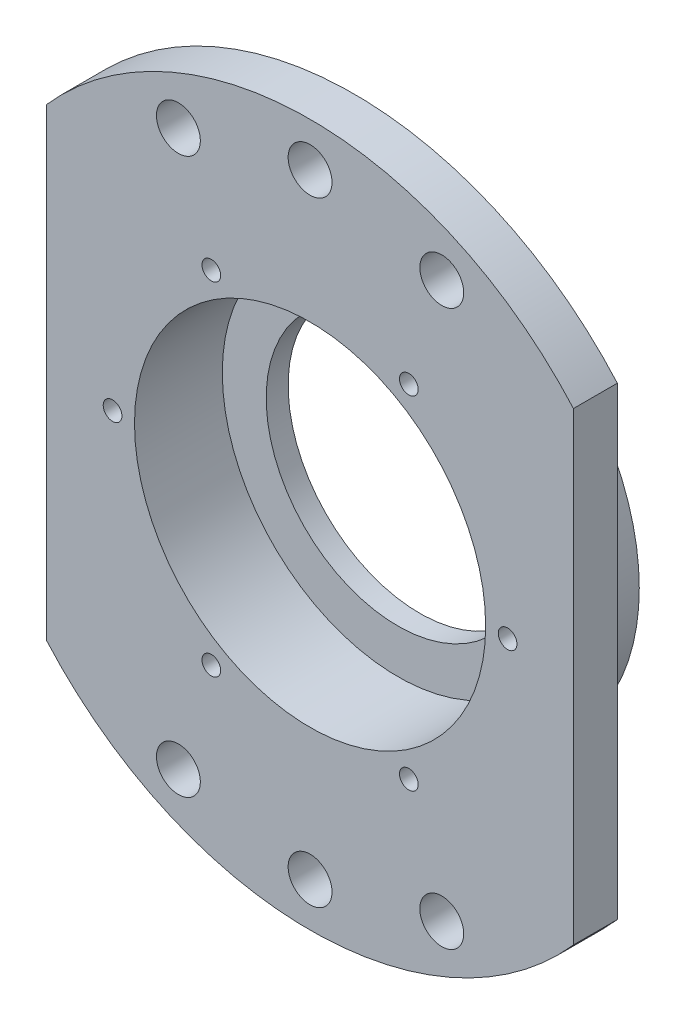
SolidWorks part; units mm, degrees
material "6061-T6 (SS)"
ref_plane "Front Plane" through (0, 0, 0) normal (0, 0, 1) x (1, 0, 0)
ref_plane "Top Plane" through (0, 0, 0) normal (0, 1, 0) x (1, 0, 0)
ref_plane "Right Plane" through (0, 0, 0) normal (1, 0, 0) x (0, 0, -1)
ref_plane "Plane1" through (0, 0, 1.5875) normal (0, 0, -1) x (-1, 0, 0)
sketch "Sketch1" plane through (0, 0, 1.5875) normal (0, 0, -1) x (-1, 0, 0)
  line L0 (38.1, -33.601) -> (38.1, 33.601)
  line L1 (-38.1, 33.601) -> (-38.1, -33.601)
  arc A0 (-38.1, -33.601) -> (38.1, -33.601) centre (0, 0) ccw
  arc A1 (38.1, 33.601) -> (-38.1, 33.601) centre (0, 0) ccw
extrude "Boss-Extrude1" add sketch "Sketch1" against normal blind 6.35
sketch "Sketch2" plane through (0, 0, 0) normal (0, 1, 0) x (1, 0, 0)
  line L0 (31.75, 7.9375) -> (0, 7.9375)
  line L1 (0, 7.9375) -> (0, -1.5875)
  line L2 (0, -1.5875) -> (31.75, -1.5875)
  line L3 (31.75, -1.5875) -> (31.75, 7.9375)
  line L4 (0, 7.9375) -> (0, -1.5875) construction
revolve "Revolve1" add sketch "Sketch2" angle 360 about L4
hole_wizard "2-4.5 Tapped Hole1" positions "Sketch8" profile "Sketch7" tap size "2-4.5" standard "ANSI Inch"
sketch "Sketch8" plane through (0, 0, 7.9375) normal (0, 0, 1) x (1, 0, 0)
  point P0 (0, 0)
sketch "Sketch7" plane through (0, 0, 7.9375) normal (1, 0, 0) x (0, -1, 0)
  line L0 (0, 0) -> (0, 15.875)
  line L1 (0, 15.875) -> (19.05, 15.875)
  line L3 (19.05, 15.875) -> (19.05, 12.7)
  line L4 (19.05, 12.7) -> (25.4, 12.7)
  line L5 (25.4, 12.7) -> (25.4, 0)
  line L7 (25.4, 0) -> (0, 0)
  line L11 (0, -6.35) -> (0, 107.95) construction
  dimension "Thru Tap Drill Dia." = 38.1
  dimension "Thru Tap Drill Depth" = 15.875
  dimension "Thread Major Dia." = 50.8
  dimension "Thread Depth" = 12.7
ref_plane "Plane2" through (0, 0, 7.9375) normal (0, 0, 1) x (1, 0, 0)
sketch "Sketch13" plane through (0, 0, 7.9375) normal (0, 0, 1) x (1, 0, 0)
  circle A0 centre (0, 44.45) radius 3.175
  circle A1 centre (0, 0) radius 25.4 construction
  dimension "D1" = 6.35
  dimension "D2" = 44.45
extrude "Cut-Extrude1" cut sketch "Sketch13" against normal through all
pattern_circular "CirPattern1" count 2 over 360 about axis through (0, 0, 0) along (0, 0, 1) of "Cut-Extrude1"
hole_wizard "#6-32 Tapped Hole1" positions "Sketch14" profile "Sketch15" tap size "#6-32" standard "ANSI Inch" end condition through all
sketch "Sketch14" plane through (0, 0, 7.9375) normal (0, 0, 1) x (1, 0, 0)
  circle A0 centre (0, 0) radius 19.05 construction
  point P0 (28.575, 0)
  dimension "D1" = 0
  dimension "D2" = 28.575
sketch "Sketch15" plane through (28.575, 0, 7.9375) normal (1, 0, 0) x (0, -1, 0)
  line L0 (0, 0) -> (0, 15.875)
  line L1 (0, 15.875) -> (1.3525, 15.875)
  line L2 (1.3525, 15.875) -> (1.3525, 0)
  line L5 (1.3525, 0) -> (0, 0)
  line L11 (0, -6.35) -> (0, 107.95) construction
  dimension "Thru Tap Drill Dia." = 2.7051
  dimension "Thru Tap Drill Depth" = 15.875
cosmetic thread "Hole Thread1" parameters "D2"=3.5052
pattern_circular "CirPattern2" count 6 over 360 about axis through (0, 0, 0) along (0, 0, 1) of "#6-32 Tapped Hole1"
hole_wizard "1/4 (0.25) Diameter Hole1" positions "Sketch16" profile "Sketch17" hole size "1/4" standard "ANSI Inch" end condition through all
sketch "Sketch16" plane through (0, 0, 7.9375) normal (0, 0, 1) x (1, 0, 0)
  circle A0 centre (0, 0) radius 19.05 construction
  point P0 (-19.05, 40.1609)
  dimension "D1" = 44.45
  dimension "D2" = 19.05
sketch "Sketch17" plane through (-19.05, 40.1609, 7.9375) normal (1, 0, 0) x (0, -1, 0)
  line L0 (0, 0) -> (0, 15.875)
  line L1 (0, 15.875) -> (3.175, 15.875)
  line L2 (3.175, 15.875) -> (3.175, 0)
  line L5 (3.175, 0) -> (0, 0)
  line L11 (0, -6.35) -> (0, 107.95) construction
  dimension "Thru Hole Dia." = 6.35
  dimension "Thru Hole Depth" = 15.875
hole_wizard "1/4 (0.25) Diameter Hole2" positions "Sketch18" profile "Sketch19" hole size "1/4" standard "ANSI Inch" end condition through all
sketch "Sketch18" plane through (0, 0, 7.9375) normal (0, 0, 1) x (1, 0, 0)
  circle A0 centre (0, 0) radius 19.05 construction
  circle A1 centre (0, 0) radius 25.4 construction
  point P0 (19.05, 40.1609)
  point P2 (19.05, -40.1609)
  point P4 (-19.05, -40.1609)
  dimension "D1" = 19.05
  dimension "D3" = 19.05
  dimension "D2" = 19.05
  dimension "D4" = 44.45
  dimension "D5" = 44.45
  dimension "D6" = 44.45
sketch "Sketch19" plane through (19.05, 40.1609, 7.9375) normal (1, 0, 0) x (0, -1, 0)
  line L0 (0, 0) -> (0, 15.875)
  line L1 (0, 15.875) -> (3.175, 15.875)
  line L2 (3.175, 15.875) -> (3.175, 0)
  line L5 (3.175, 0) -> (0, 0)
  line L11 (0, -6.35) -> (0, 107.95) construction
  dimension "Thru Hole Dia." = 6.35
  dimension "Thru Hole Depth" = 15.875
